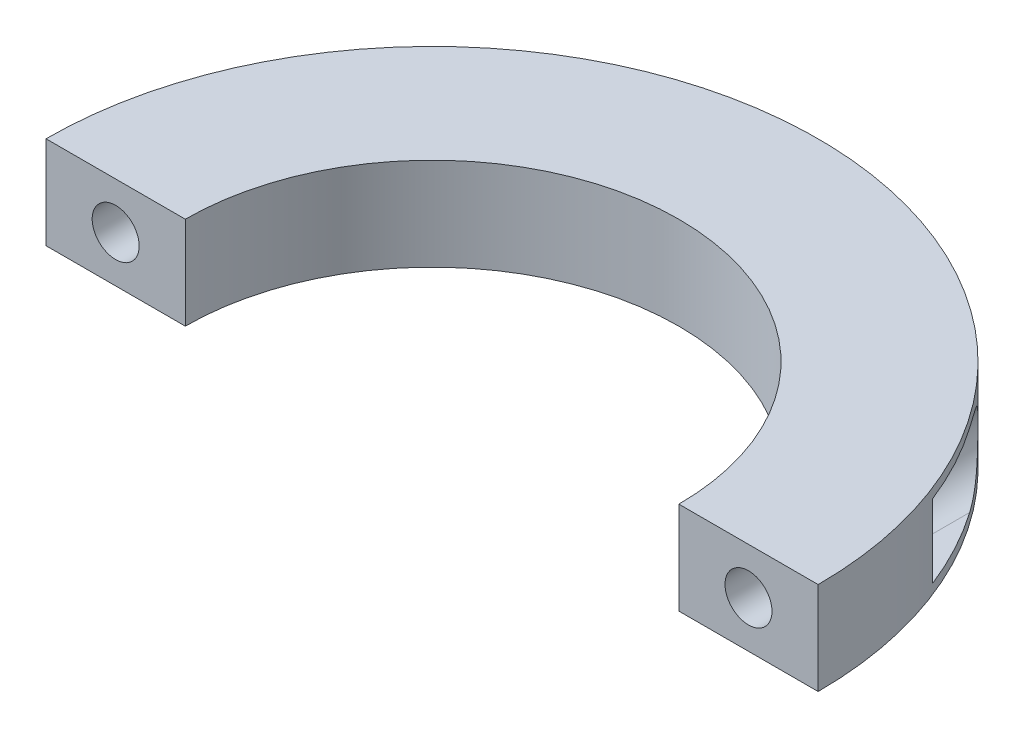
SolidWorks part; units mm, degrees
ref_plane "Front Plane" through (0, 0, 0) normal (0, 0, 1) x (1, 0, 0)
ref_plane "Top Plane" through (0, 0, 0) normal (0, 1, 0) x (1, 0, 0)
ref_plane "Right Plane" through (0, 0, 0) normal (1, 0, 0) x (0, 0, -1)
sketch "Sketch1" plane through (0, 0, 0) normal (0, 1, 0) x (1, 0, 0)
  line L0 (-19.175, 0) -> (-30, 0)
  line L1 (0, 0) -> (0, 29.2011) construction
  line L2 (19.175, 0) -> (30, 0)
  arc A0 (-19.175, 0) -> (19.175, 0) centre (0, 0) cw
  arc A1 (-30, 0) -> (30, 0) centre (0, 0) cw
  dimension "D1" = 38.35
  dimension "D2" = 60
extrude "Boss-Extrude1" add sketch "Sketch1" along normal blind 7.2
sketch "Sketch2" plane through (0, 0, 0) normal (0, 0, 1) x (1, 0, 0)
  line L0 (-30, 3.6) -> (-19.175, 3.6) construction
  line L1 (-30, 7.2) -> (-30, 0) construction
  line L2 (-19.175, 7.2) -> (-19.175, 0) construction
  line L3 (-24.5875, 7.2) -> (-24.5875, 0) construction
  line L4 (-30, 7.2) -> (-19.175, 7.2) construction
  line L5 (-30, 0) -> (-19.175, 0) construction
  line L6 (19.175, 3.6) -> (30, 3.6) construction
  line L7 (19.175, 7.2) -> (19.175, 0) construction
  line L8 (30, 7.2) -> (30, 0) construction
  line L9 (24.5875, 7.2) -> (24.5875, 0) construction
  line L10 (19.175, 7.2) -> (30, 7.2) construction
  line L11 (19.175, 0) -> (30, 0) construction
  circle A0 centre (-24.5875, 3.6) radius 1.825
  circle A1 centre (24.5875, 3.6) radius 1.825
  dimension "D1" = 3.65
extrude "Cut-Extrude1" cut sketch "Sketch2" against normal blind 47.2
sketch3d "3DSketch3"
  spline S0 degree 3 poles (26.4125, 3.5141, -14.226) (26.4125, 3.7718, -14.226) (26.3873, 3.9381, -14.2729) (26.3067, 4.2309, -14.421) (26.2515, 4.3603, -14.5215) (26.1291, 4.5851, -14.7406) (26.0603, 4.6836, -14.8621) (25.9156, 4.8568, -15.113) (25.8397, 4.9316, -15.2425) (25.6028, 5.1305, -15.6395) (25.4313, 5.2293, -15.9172) (25.0778, 5.3681, -16.4685) (24.8946, 5.409, -16.7443) (24.5146, 5.4335, -17.2959) (24.3167, 5.4163, -17.5729) (24.0214, 5.338, -17.9722) (23.9228, 5.3031, -18.1032) (23.7257, 5.2124, -18.3607) (23.6268, 5.1561, -18.4878) (23.4355, 5.0203, -18.7297) (23.3426, 4.9408, -18.8452) (23.1651, 4.7508, -19.063) (23.082, 4.6417, -19.1633) (22.9367, 4.3914, -19.3371) (22.8741, 4.2487, -19.4108) (22.8087, 4.0159, -19.4875) (22.7914, 3.9338, -19.5078) (22.7684, 3.7689, -19.5346) (22.7625, 3.6854, -19.5414) (22.7625, 3.5162, -19.5415) (22.7685, 3.4304, -19.5345) (22.7915, 3.2652, -19.5076) (22.8086, 3.1845, -19.4877) (22.8747, 2.9492, -19.4101) (22.9372, 2.8074, -19.3365) (23.1563, 2.431, -19.0745) (23.3417, 2.2461, -18.8484) (23.7228, 1.976, -18.3664) (23.924, 1.8877, -18.1039) (24.3177, 1.7836, -17.5716) (24.5118, 1.7665, -17.2998) (24.8939, 1.7908, -16.7453) (25.0793, 1.8323, -16.4662) (25.4325, 1.9713, -15.9153) (25.6027, 2.0693, -15.6396) (25.9204, 2.3363, -15.1072) (26.0693, 2.5046, -14.8477) (26.2518, 2.8404, -14.521) (26.3069, 2.9697, -14.4205) (26.3674, 3.1898, -14.3095) (26.3841, 3.2688, -14.2787) (26.4065, 3.4309, -14.2372) (26.4125, 3.5141, -14.226) (26.4125, 3.7718, -14.226) (26.3873, 3.9381, -14.2729) knots -0.015625 -0.015625 0 0 0.03125 0.03125 0.0625 0.0625 0.09375 0.09375 0.125 0.125 0.1875 0.1875 0.25 0.25 0.3125 0.3125 0.34375 0.34375 0.375 0.375 0.40625 0.40625 0.4375 0.4375 0.46875 0.46875 0.484375 0.484375 0.5 0.5 0.515625 0.515625 0.53125 0.53125 0.5625 0.5625 0.625 0.625 0.6875 0.6875 0.75 0.75 0.8125 0.8125 0.875 0.875 0.9375 0.9375 0.96875 0.96875 0.984375 0.984375 1 1 1.03125 1.03125 1.0625 only from (26.4125, 3.6, -14.226) to (26.4125, 3.6, -14.226) construction
  point P0 (25.0906, 1.8457, -16.4457)
ref_plane "Plane3" through (0, 0, -16.4457) normal (0, 0, -1) x (0, -1, 0)
sketch "Sketch3" plane through (0, 0, -16.4457) normal (0, 0, -1) x (0, -1, 0)
  circle A0 centre (-3.6, 24.5875) radius 2.85
  circle A1 centre (-3.6, -24.5875) radius 2.85
  dimension "D1" = 5.7
extrude "Cut-Extrude3" cut sketch "Sketch3" against normal blind 5.5 and the other way blind 5
sketch3d "3DSketch4"
  circle A0 centre (-24.5875, 3.6, -10.9457) radius 1.825 construction
  point P0 (-22.9036, 2.8964, -10.9457)
  point P3 (-24.5875, 3.6, -9.1207)
sketch3d "3DSketch5"
  circle A0 centre (-24.5875, 3.6, -10.9457) radius 1.825 construction
  point P0 (-23.9685, 1.8832, -10.9457)
  point P3 (-24.5875, 3.6, -9.1207)
ref_plane "Plane5" through (0, 0, -10.9457) normal (0, 0, -1) x (1, 0, 0)
sketch "Sketch4" plane through (0, 0, -10.9457) normal (0, 0, -1) x (1, 0, 0)
  line L6 (0, 4.0307) -> (0, -13.6162) construction
  line L12 (-30, -0.75) -> (-30, -6.45)
  line L15 (-30, -7.2) -> (-30, 0) construction
  line L17 (-24.5875, -0.75) -> (-30, -0.75)
  line L18 (-30, -6.45) -> (-24.5875, -6.45)
  line L19 (30, -0.75) -> (30, -6.45)
  line L20 (24.5875, -0.75) -> (30, -0.75)
  line L21 (30, -6.45) -> (24.5875, -6.45)
  arc A6 (-24.5875, -0.75) -> (-24.5875, -6.45) centre (-24.5875, -3.6) cw
  circle A7 centre (-24.5875, -3.6) radius 2.85 construction
  circle A8 centre (-24.5875, -3.6) radius 2.85 construction
  arc A9 (24.5875, -0.75) -> (24.5875, -6.45) centre (24.5875, -3.6) ccw
extrude "Cut-Extrude4" cut sketch "Sketch4" along normal blind 20
